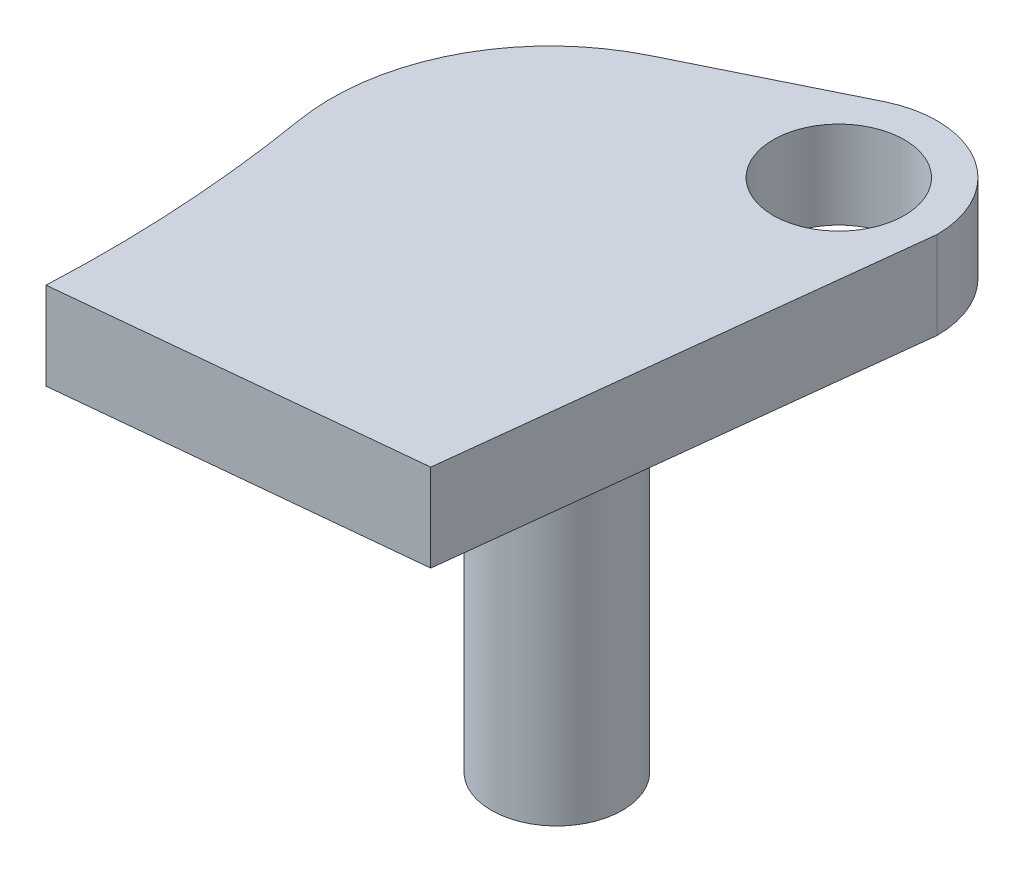
SolidWorks part; units mm, degrees
ref_plane "Front Plane" through (0, 0, 0) normal (0, 0, 1) x (1, 0, 0)
ref_plane "Top Plane" through (0, 0, 0) normal (0, 1, 0) x (1, 0, 0)
ref_plane "Right Plane" through (0, 0, 0) normal (1, 0, 0) x (0, 0, -1)
sketch "Sketch2" plane through (0, 0, 0) normal (0, 1, 0) x (1, 0, 0)
  line L1 (12.0004, 5.4685) -> (13.1829, 15.8647)
  line L5 (9.9788, 17.9024) -> (2.7988, 14.3743)
  line L10 (12.0004, 5.4685) -> (4.0004, 4.673)
  circle A1 centre (10.9329, 15.8647) radius 2.25
  circle A2 centre (10.9329, 15.8647) radius 1.5
  arc A4 (4.0004, 4.673) -> (2.7988, 14.3743) centre (-24.968, 6.0101) ccw
  dimension "D1" = 4.5
  dimension "D2" = 8
  dimension "D3" = 8
  dimension "D4" = 3
extrude "Boss-Extrude1" add sketch "Sketch2" along normal blind 2
sketch "Sketch3" plane through (0, 0, 0) normal (0, 1, 0) x (1, 0, 0)
  line L2 (12.0004, 5.4685) -> (13.1829, 15.8647) construction
  circle A0 centre (10.4876, 9.8647) radius 1.5
  circle A2 centre (10.9329, 15.8647) radius 1.5 construction
  dimension "D2" = 3
  dimension "D1" = 6
  dimension "D3" = 2
extrude "Boss-Extrude2" add sketch "Sketch3" against normal blind 7
fillet "Fillet1" radius 5 1 edges at (2.7988, 1, -14.3743)
